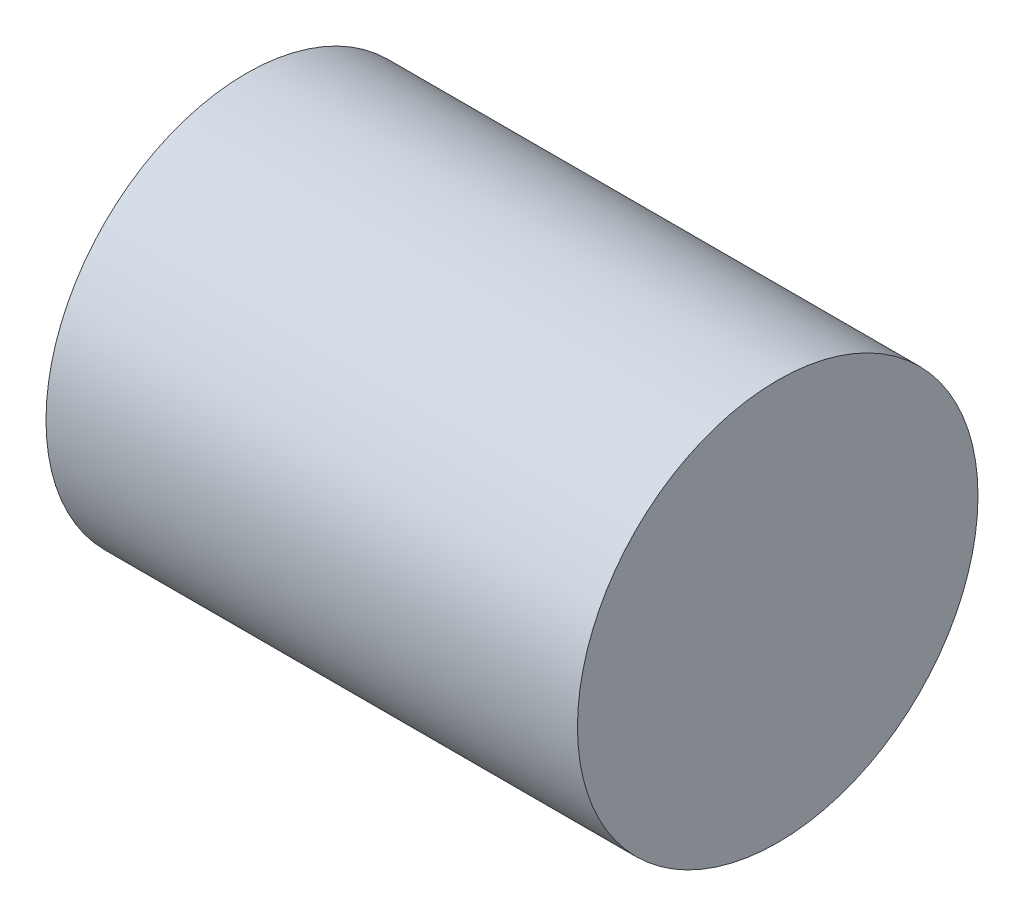
SolidWorks part; units mm, degrees
ref_plane "Front Plane" through (0, 0, 0) normal (0, 0, 1) x (1, 0, 0)
ref_plane "Top Plane" through (0, 0, 0) normal (0, 1, 0) x (1, 0, 0)
ref_plane "Right Plane" through (0, 0, 0) normal (1, 0, 0) x (0, 0, -1)
sketch "CurveSketch" plane through (0, 0, 0) normal (1, 0, 0) x (0, 0, -1)
  circle A0 centre (9.173, -2.419) radius 8.719
  dimension "D1" = 8.719
extrude "CurveBoss" add sketch "CurveSketch" against normal blind 23.137
